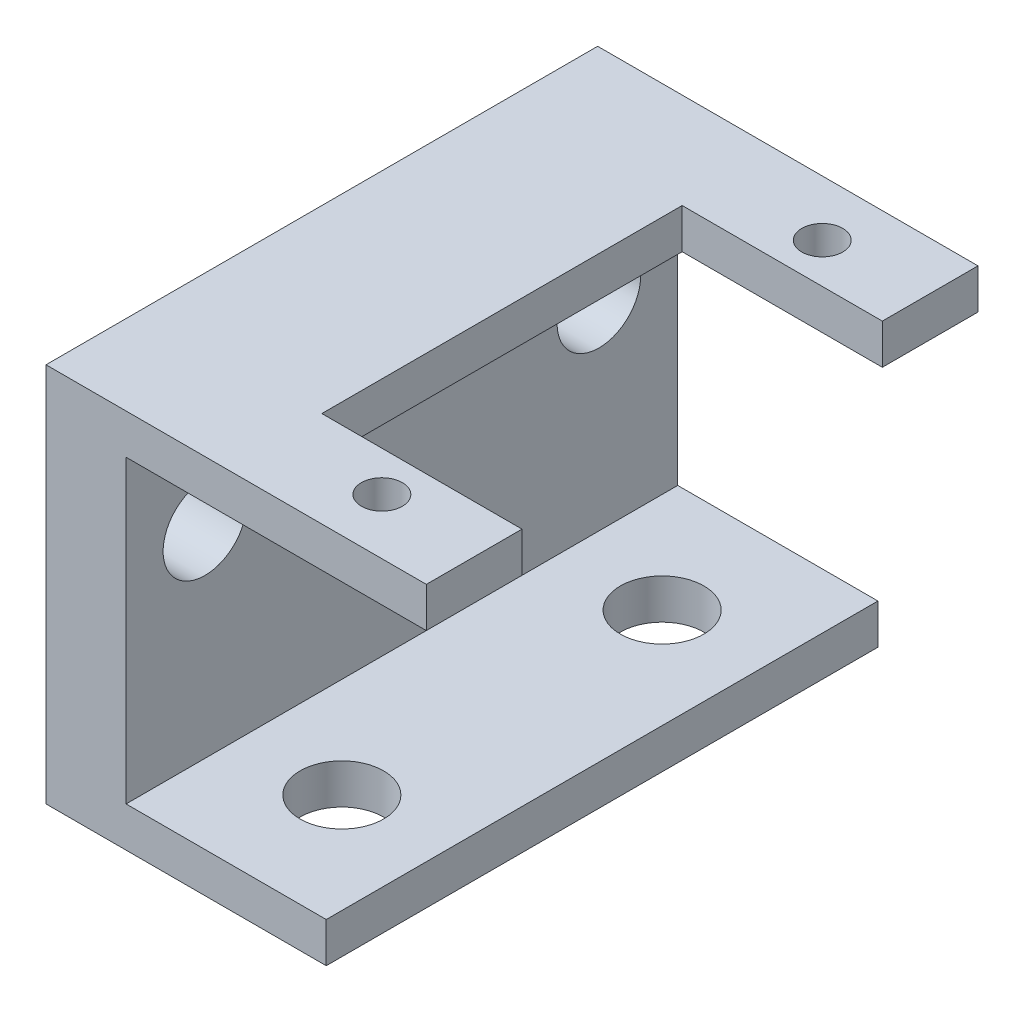
SolidWorks part; units mm, degrees
ref_plane "Front Plane" through (0, 0, 0) normal (0, 0, 1) x (1, 0, 0)
ref_plane "Top Plane" through (0, 0, 0) normal (0, 1, 0) x (1, 0, 0)
ref_plane "Right Plane" through (0, 0, 0) normal (1, 0, 0) x (0, 0, -1)
sketch "Sketch1" plane through (0, 0, 0) normal (0, 0, 1) x (1, 0, 0)
  line L1 (0, 0) -> (17.78, 0)
  line L2 (0, 0) -> (0, 2.54)
  line L3 (0, 2.54) -> (17.78, 2.54)
  line L4 (17.78, 0) -> (17.78, 2.54)
  line L5 (0, 2.54) -> (5.08, 2.54)
  line L6 (0, 2.54) -> (0, 21.59)
  line L7 (0, 21.59) -> (5.08, 21.59)
  line L8 (5.08, 2.54) -> (5.08, 21.59)
  line L9 (0, 21.59) -> (24.13, 21.59)
  line L10 (0, 21.59) -> (0, 24.13)
  line L11 (0, 24.13) -> (24.13, 24.13)
  line L12 (24.13, 21.59) -> (24.13, 24.13)
  dimension "D1" = 5.08
  dimension "D2" = 12.7
  dimension "D3" = 19.05
  dimension "D4" = 2.54
  dimension "D5" = 2.54
  dimension "D6" = 19.05
extrude "Boss-Extrude1" add sketch "Sketch1" along normal blind 35 contours L9 L12 L11 L10 L7 | L2 L1 L4 L3
hole_wizard "Ø5.0mm Dowel Hole1" positions "Sketch2" profile "Sketch3" hole size "Ø5.0" standard "ANSI Metric" end condition through all
sketch "Sketch2" plane through (5.08, 0, 0) normal (1, 0, 0) x (0, 0, -1)
  line L3 (-35, 2.54) -> (0, 2.54) construction
  line L6 (-30, 15.24) -> (-5, 15.24) construction
  line L8 (-35, 0) -> (0, 0) construction
  point P0 (-30, 15.24)
  point P2 (-5, 15.24)
  point P30 (-17.5, 0)
  point P31 (-17.5, 15.24)
  dimension "D1" = 25
  dimension "D3" = 12.7
sketch "Sketch3" plane through (5.08, 15.24, 30) normal (0, 1, 0) x (0, 0, -1)
  line L0 (0, 0) -> (0, 5.08)
  line L1 (0, 5.08) -> (2.65, 5.08)
  line L2 (2.65, 5.08) -> (2.65, 0)
  line L5 (2.65, 0) -> (0, 0)
  line L11 (0, -6.35) -> (0, 107.95) construction
  dimension "Thru Hole Dia." = 5.3
  dimension "Thru Hole Depth" = 5.08
hole_wizard "Ø5.0mm Dowel Hole2" positions "Sketch4" profile "Sketch5" hole size "Ø5.0" standard "ANSI Metric"
sketch "Sketch4" plane through (0, 2.54, 0) normal (0, 1, 0) x (1, 0, 0)
  line L2 (11.43, -7.34) -> (11.43, -27.66) construction
  line L5 (5.08, -35) -> (5.08, 0) construction
  line L6 (17.78, -35) -> (17.78, 0) construction
  point P0 (11.43, -27.66)
  point P2 (11.43, -7.34)
  point P25 (17.78, -17.5)
  point P26 (11.43, -17.5)
  dimension "D1" = 20.32
  dimension "D2" = 6.35
sketch "Sketch5" plane through (11.43, 2.54, 27.66) normal (1, 0, 0) x (0, 0, 1)
  line L0 (0, 0) -> (0, 2.54)
  line L1 (0, 2.54) -> (2.65, 2.54)
  line L2 (2.65, 2.54) -> (2.65, 0)
  line L5 (2.65, 0) -> (0, 0)
  line L11 (0, -6.35) -> (0, 107.95) construction
  dimension "Thru Hole Dia." = 5.3
  dimension "Thru Hole Depth" = 2.54
sketch "Sketch6" plane through (0, 24.13, 0) normal (0, 1, 0) x (1, 0, 0)
  line L0 (24.13, -35) -> (24.13, 0) construction
  line L1 (24.13, -6.07) -> (11.43, -6.07)
  line L2 (24.13, -6.07) -> (24.13, -28.93)
  line L3 (24.13, -28.93) -> (11.43, -28.93)
  line L4 (11.43, -6.07) -> (11.43, -28.93)
  line L5 (0, 0) -> (24.13, 0) construction
  line L6 (0, -35) -> (24.13, -35) construction
  line L9 (17.78, -6.07) -> (17.78, 0) construction
  line L10 (17.78, -28.93) -> (17.78, -35) construction
  dimension "D2" = 12.7
  dimension "D1" = 22.86
extrude "Cut-Extrude1" cut sketch "Sketch6" against normal up to next contours L2 L1 L4 L3
hole_wizard "M2 Clearance Hole1" positions "Sketch7" profile "Sketch8" hole size "M2" standard "ANSI Metric"
sketch "Sketch7" plane through (0, 24.13, 0) normal (0, 1, 0) x (1, 0, 0)
  line L0 (17.78, -28.93) -> (17.78, -35) construction
  line L1 (17.78, -6.07) -> (17.78, 0) construction
  line L2 (11.43, -6.07) -> (11.43, -28.93) construction
  point P0 (17.78, -31.47)
  point P4 (17.78, -3.53)
  point P13 (11.43, -17.5)
  dimension "D1" = 13.97
  dimension "D2" = 13.97
sketch "Sketch8" plane through (17.78, 24.13, 31.47) normal (1, 0, 0) x (0, 0, 1)
  line L0 (0, 0) -> (0, 2.54)
  line L1 (0, 2.54) -> (1.3, 2.54)
  line L2 (1.3, 2.54) -> (1.3, 0)
  line L5 (1.3, 0) -> (0, 0)
  line L11 (0, -6.35) -> (0, 107.95) construction
  dimension "Thru Hole Dia." = 2.6
  dimension "Thru Hole Depth" = 2.54
equation "\"wall thicc\"= 2.5mm"
equation "\"press fit\"= 0.3mm"
equation "\"shaft thick\"= 5mm + \"press fit\""
equation "\"D1@Sketch1\"=\"wall thicc\"*2"
equation "\"D4@Sketch1\"=\"wall thicc\""
equation "\"D5@Sketch1\"=\"wall thicc\""
equation "\"servo width\"= 22.5mm"
equation "\"D1@Sketch6\"=\"servo width\"+\"press fit\""
equation "\"servo length\"= 12.5mm"
equation "\"D2@Sketch6\"=\"servo length\"+\"press fit\""
equation "\"servo hole spacing\"= 13.9mm"
equation "\"D1@Sketch7\"=\"servo hole spacing\""
equation "\"D2@Sketch7\"=\"servo hole spacing\""
